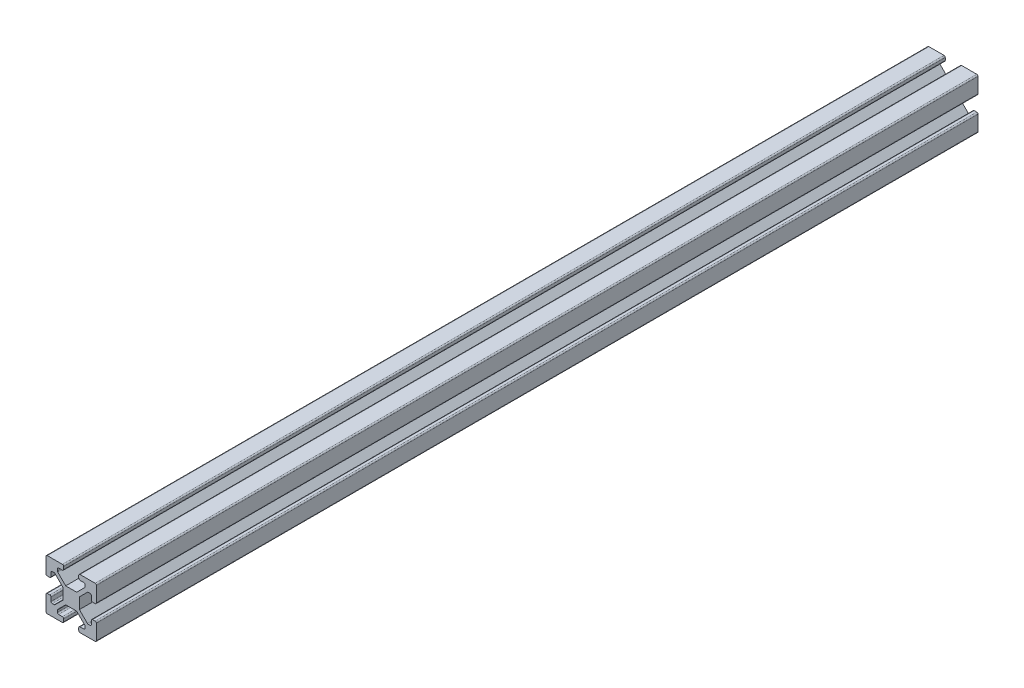
SolidWorks part; units mm, degrees
material "3.1645 (EN AW-2007)"
ref_plane "Front" through (0, 0, 0) normal (0, 0, 1) x (1, 0, 0)
ref_plane "Top" through (0, 0, 0) normal (0, 1, 0) x (1, 0, 0)
ref_plane "Right" through (0, 0, 0) normal (1, 0, 0) x (0, 0, -1)
sketch "草图1" plane through (0, 0, 0) normal (0, 0, 1) x (1, 0, 0)
  line L0 (6.5, 0) -> (0.5, 0)
  line L1 (20, -0.5) -> (20, -6.5)
  line L2 (19.5, -20) -> (13.5, -20)
  line L3 (20, -13.5) -> (20, -19.5)
  line L4 (13, -19.5) -> (13, -18.5)
  line L5 (13.5, -18) -> (15, -18)
  line L6 (15.5, -17.5) -> (15.5, -16.7791)
  line L7 (19.5, -7) -> (18.5, -7)
  line L8 (10, 0) -> (10, -26.2948) construction
  line L9 (18, -6.5) -> (18, -5)
  line L10 (17.5, -4.5) -> (16.7791, -4.5)
  line L11 (17.5, -15.5) -> (16.7791, -15.5)
  line L12 (18, -13.5) -> (18, -15)
  line L13 (19.5, -13) -> (18.5, -13)
  line L15 (0, -10) -> (20, -10) construction
  line L23 (4.5, -17.5) -> (4.5, -16.7791)
  line L24 (6.5, -18) -> (5, -18)
  line L25 (7, -19.5) -> (7, -18.5)
  line L27 (0.5, -20) -> (6.5, -20)
  line L29 (10, -20) -> (10, 6.2948) construction
  line L33 (0.5, -13) -> (1.5, -13)
  line L34 (2, -13.5) -> (2, -15)
  line L35 (2.5, -15.5) -> (3.2209, -15.5)
  line L36 (2.5, -4.5) -> (3.2209, -4.5)
  line L37 (2, -6.5) -> (2, -5)
  line L38 (0.5, -7) -> (1.5, -7)
  line L40 (7, -0.5) -> (7, -1.5)
  line L41 (6.5, -2) -> (5, -2)
  line L42 (4.5, -2.5) -> (4.5, -3.2209)
  line L43 (3.5745, -4.6464) -> (6.7416, -7.8136)
  line L44 (6.7416, -7.8136) -> (6.7416, -12.1864)
  line L45 (15.5, -2.5) -> (15.5, -3.2209)
  line L46 (13.5, -2) -> (15, -2)
  line L47 (13, -0.5) -> (13, -1.5)
  line L48 (19.5, 0) -> (13.5, 0)
  line L50 (10.3536, -10.3536) -> (20, -20) construction
  line L51 (4.6464, -3.5745) -> (7.8136, -6.7416)
  line L52 (7.8136, -6.7416) -> (12.1864, -6.7416)
  line L53 (0, -20) -> (9.6464, -10.3536) construction
  line L54 (15.3536, -3.5745) -> (12.1864, -6.7416)
  line L55 (13.2584, -7.8136) -> (13.2584, -12.1864)
  line L56 (16.4255, -4.6464) -> (13.2584, -7.8136)
  line L57 (10, 0) -> (10, -26.2948) construction
  line L58 (10, -20) -> (10, 6.2948) construction
  line L59 (16.4255, -15.3536) -> (13.2584, -12.1864)
  line L60 (15.3536, -16.4255) -> (12.3328, -13.4048)
  line L61 (8.0207, -13.2584) -> (11.9793, -13.2584)
  line L62 (4.6464, -16.4255) -> (7.6672, -13.4048)
  line L63 (3.5745, -15.3536) -> (6.7416, -12.1864)
  line L64 (0, -6.5) -> (0, -0.5)
  line L66 (0, -13.5) -> (0, -19.5)
  arc A0 (19.5, -7) -> (20, -6.5) centre (19.5, -6.5) ccw
  arc A1 (4.6464, -16.4255) -> (4.5, -16.7791) centre (5, -16.7791) ccw
  arc A2 (8.0207, -13.2584) -> (7.6672, -13.4048) centre (8.0207, -13.7584) ccw
  arc A3 (12.3328, -13.4048) -> (11.9793, -13.2584) centre (11.9793, -13.7584) ccw
  arc A4 (16.4255, -15.3536) -> (16.7791, -15.5) centre (16.7791, -15) ccw
  arc A5 (16.4255, -4.6464) -> (16.7791, -4.5) centre (16.7791, -5) cw
  arc A6 (15.3536, -16.4255) -> (15.5, -16.7791) centre (15, -16.7791) cw
  arc A7 (10.3536, -10.3536) -> (9.6464, -10.3536) centre (10, -10.7071) ccw construction
  arc A8 (15.3536, -3.5745) -> (15.5, -3.2209) centre (15, -3.2209) ccw
  arc A9 (3.5745, -15.3536) -> (3.2209, -15.5) centre (3.2209, -15) cw
  arc A10 (3.5745, -4.6464) -> (3.2209, -4.5) centre (3.2209, -5) ccw
  arc A11 (0.5, -7) -> (0, -6.5) centre (0.5, -6.5) cw
  arc A12 (2, -6.5) -> (1.5, -7) centre (1.5, -6.5) cw
  arc A13 (4.6464, -3.5745) -> (4.5, -3.2209) centre (5, -3.2209) cw
  arc A14 (2.5, -4.5) -> (2, -5) centre (2.5, -5) ccw
  arc A15 (2, -15) -> (2.5, -15.5) centre (2.5, -15) ccw
  arc A16 (1.5, -13) -> (2, -13.5) centre (1.5, -13.5) cw
  arc A17 (0.5, -13) -> (0, -13.5) centre (0.5, -13.5) ccw
  arc A18 (19.5, -13) -> (20, -13.5) centre (19.5, -13.5) cw
  arc A19 (13.5, 0) -> (13, -0.5) centre (13.5, -0.5) ccw
  arc A20 (13, -1.5) -> (13.5, -2) centre (13.5, -1.5) ccw
  arc A21 (15, -2) -> (15.5, -2.5) centre (15, -2.5) cw
  arc A22 (18, -13.5) -> (18.5, -13) centre (18.5, -13.5) cw
  arc A23 (4.5, -2.5) -> (5, -2) centre (5, -2.5) cw
  arc A24 (6.5, -2) -> (7, -1.5) centre (6.5, -1.5) ccw
  arc A25 (7, -0.5) -> (6.5, 0) centre (6.5, -0.5) ccw
  arc A26 (6.5, -18) -> (7, -18.5) centre (6.5, -18.5) cw
  arc A27 (4.5, -17.5) -> (5, -18) centre (5, -17.5) ccw
  arc A28 (17.5, -15.5) -> (18, -15) centre (17.5, -15) ccw
  arc A29 (15, -18) -> (15.5, -17.5) centre (15, -17.5) ccw
  arc A30 (13, -18.5) -> (13.5, -18) centre (13.5, -18.5) cw
  arc A31 (18, -5) -> (17.5, -4.5) centre (17.5, -5) ccw
  arc A32 (18.5, -7) -> (18, -6.5) centre (18.5, -6.5) cw
  arc A33 (19.5, 0) -> (20, -0.5) centre (19.5, -0.5) cw
  arc A34 (0.5, 0) -> (0, -0.5) centre (0.5, -0.5) ccw
  arc A35 (7, -19.5) -> (6.5, -20) centre (6.5, -19.5) cw
  arc A36 (13.5, -20) -> (13, -19.5) centre (13.5, -19.5) cw
  arc A37 (0.5, -20) -> (0, -19.5) centre (0.5, -19.5) cw
  arc A38 (20, -19.5) -> (19.5, -20) centre (19.5, -19.5) cw
  point P28 (4.5, -16.572)
  point P50 (10, -6.7416)
  point P56 (13.2584, -10)
  point P61 (6.7416, -10)
  point P62 (10, -13.2584)
  point P63 (7.8136, -13.2584)
  point P66 (12.1864, -13.2584)
  point P69 (16.572, -15.5)
  point P72 (16.572, -4.5)
  point P75 (15.5, -16.572)
  point P78 (10, -10)
  point P81 (15.5, -3.428)
  point P84 (3.428, -15.5)
  point P87 (3.428, -4.5)
  point P94 (4.5, -3.428)
  point P107 (13, 0)
  point P110 (13, -2)
  point P113 (15.5, -2)
  point P118 (4.5, -2)
  point P121 (7, -2)
  point P124 (7, 0)
  point P127 (7, -18)
  point P130 (4.5, -18)
  point P135 (15.5, -18)
  point P138 (13, -18)
  point P145 (20, 0)
  point P148 (0, 0)
  point P151 (7, -20)
  point P154 (13, -20)
  dimension "D1" = 6.7416
  dimension "D2" = 6
  dimension "D3" = 2
extrude "凸台-拉伸1" add sketch "草图1" along normal blind 350
